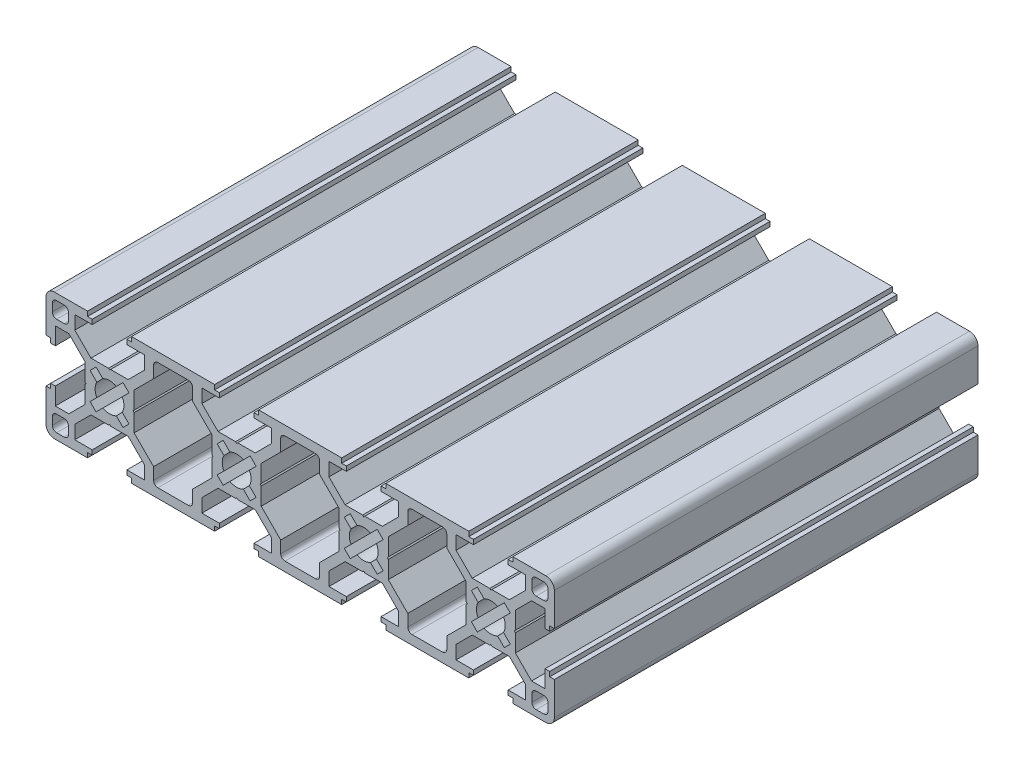
SolidWorks part; units mm, degrees
material "Aluminium"
ref_plane "Front Plane" through (0, 0, 0) normal (0, 0, 1) x (1, 0, 0)
ref_plane "Top Plane" through (0, 0, 0) normal (0, 1, 0) x (1, 0, 0)
ref_plane "Right Plane" through (0, 0, 0) normal (1, 0, 0) x (0, 0, -1)
sketch "Sketch1" plane through (0, 0, 0) normal (0, 0, 1) x (1, 0, 0)
  line L0 (-58.5, 10.7) -> (-58.5, 12.5)
  line L1 (-57.5, 13.5) -> (-55.7, 13.5)
  line L2 (-54.7, 12.5) -> (-54.7, 10.7)
  line L3 (-55.7, 9.7) -> (-57.5, 9.7)
  line L4 (-41.9951, -1.5907) -> (-40.4041, -3.1817)
  line L5 (-40.4041, -3.1817) -> (-41.8183, -4.5959)
  line L6 (-41.8183, -4.5959) -> (-43.4093, -3.0049)
  line L7 (-46.5907, -3.0049) -> (-48.1817, -4.5959)
  line L8 (-48.1817, -4.5959) -> (-49.5959, -3.1817)
  line L9 (-49.5959, -3.1817) -> (-48.0049, -1.5907)
  line L10 (-48.0049, 1.5907) -> (-49.5959, 3.1817)
  line L11 (-49.5959, 3.1817) -> (-48.1817, 4.5959)
  line L12 (-48.1817, 4.5959) -> (-46.5907, 3.0049)
  line L13 (-43.4093, 3.0049) -> (-41.8183, 4.5959)
  line L14 (-41.8183, 4.5959) -> (-40.4041, 3.1817)
  line L15 (-40.4041, 3.1817) -> (-41.9951, 1.5907)
  line L16 (-58.5, -12.5) -> (-58.5, -10.7)
  line L17 (-57.5, -9.7) -> (-55.7, -9.7)
  line L18 (-54.7, -10.7) -> (-54.7, -12.5)
  line L19 (-55.7, -13.5) -> (-57.5, -13.5)
  line L20 (-20.55, 0) -> (-20.8, -0.25)
  line L21 (-20.8, -0.25) -> (-20.8, -4.3858)
  line L22 (-20.8, -4.3858) -> (-25.4, -8.9858)
  line L23 (-25.4, -8.9858) -> (-25.4, -11.8)
  line L24 (-26.4, -12.8) -> (-33.6, -12.8)
  line L25 (-34.6, -11.8) -> (-34.6, -8.9858)
  line L26 (-34.6, -8.9858) -> (-39.2, -4.3858)
  line L27 (-39.2, -4.3858) -> (-39.2, -0.25)
  line L28 (-39.2, -0.25) -> (-39.45, 0)
  line L29 (-39.45, 0) -> (-39.2, 0.25)
  line L30 (-39.2, 0.25) -> (-39.2, 4.3858)
  line L31 (-39.2, 4.3858) -> (-34.6, 8.9858)
  line L32 (-34.6, 8.9858) -> (-34.6, 11.8)
  line L33 (-33.6, 12.8) -> (-26.4, 12.8)
  line L34 (-25.4, 11.8) -> (-25.4, 8.9858)
  line L35 (-25.4, 8.9858) -> (-20.8, 4.3858)
  line L36 (-20.8, 4.3858) -> (-20.8, 0.25)
  line L37 (-20.8, 0.25) -> (-20.55, 0)
  line L38 (-11.9951, -1.5907) -> (-10.4041, -3.1817)
  line L39 (-10.4041, -3.1817) -> (-11.8183, -4.5959)
  line L40 (-11.8183, -4.5959) -> (-13.4093, -3.0049)
  line L41 (-16.5907, -3.0049) -> (-18.1817, -4.5959)
  line L42 (-18.1817, -4.5959) -> (-19.5959, -3.1817)
  line L43 (-19.5959, -3.1817) -> (-18.0049, -1.5907)
  line L44 (-18.0049, 1.5907) -> (-19.5959, 3.1817)
  line L45 (-19.5959, 3.1817) -> (-18.1817, 4.5959)
  line L46 (-18.1817, 4.5959) -> (-16.5907, 3.0049)
  line L47 (-13.4093, 3.0049) -> (-11.8183, 4.5959)
  line L48 (-11.8183, 4.5959) -> (-10.4041, 3.1817)
  line L49 (-10.4041, 3.1817) -> (-11.9951, 1.5907)
  line L50 (11.9951, 1.5907) -> (10.4041, 3.1817)
  line L51 (10.4041, 3.1817) -> (11.8183, 4.5959)
  line L52 (11.8183, 4.5959) -> (13.4093, 3.0049)
  line L53 (16.5907, 3.0049) -> (18.1817, 4.5959)
  line L54 (18.1817, 4.5959) -> (19.5959, 3.1817)
  line L55 (19.5959, 3.1817) -> (18.0049, 1.5907)
  line L56 (18.0049, -1.5907) -> (19.5959, -3.1817)
  line L57 (19.5959, -3.1817) -> (18.1817, -4.5959)
  line L58 (18.1817, -4.5959) -> (16.5907, -3.0049)
  line L59 (13.4093, -3.0049) -> (11.8183, -4.5959)
  line L60 (11.8183, -4.5959) -> (10.4041, -3.1817)
  line L61 (10.4041, -3.1817) -> (11.9951, -1.5907)
  line L62 (20.8, -0.25) -> (20.55, 0)
  line L63 (20.55, 0) -> (20.8, 0.25)
  line L64 (20.8, 0.25) -> (20.8, 4.3858)
  line L65 (20.8, 4.3858) -> (25.4, 8.9858)
  line L66 (25.4, 8.9858) -> (25.4, 11.8)
  line L67 (26.4, 12.8) -> (33.6, 12.8)
  line L68 (34.6, 11.8) -> (34.6, 8.9858)
  line L69 (34.6, 8.9858) -> (39.2, 4.3858)
  line L70 (39.2, 4.3858) -> (39.2, 0.25)
  line L71 (39.2, 0.25) -> (39.45, 0)
  line L72 (39.45, 0) -> (39.2, -0.25)
  line L73 (39.2, -0.25) -> (39.2, -4.3858)
  line L74 (39.2, -4.3858) -> (34.6, -8.9858)
  line L75 (34.6, -8.9858) -> (34.6, -11.8)
  line L76 (33.6, -12.8) -> (26.4, -12.8)
  line L77 (25.4, -11.8) -> (25.4, -8.9858)
  line L78 (25.4, -8.9858) -> (20.8, -4.3858)
  line L79 (20.8, -4.3858) -> (20.8, -0.25)
  line L80 (58.5, -10.7) -> (58.5, -12.5)
  line L81 (57.5, -13.5) -> (55.7, -13.5)
  line L82 (54.7, -12.5) -> (54.7, -10.7)
  line L83 (55.7, -9.7) -> (57.5, -9.7)
  line L84 (41.9951, 1.5907) -> (40.4041, 3.1817)
  line L85 (40.4041, 3.1817) -> (41.8183, 4.5959)
  line L86 (41.8183, 4.5959) -> (43.4093, 3.0049)
  line L87 (46.5907, 3.0049) -> (48.1817, 4.5959)
  line L88 (48.1817, 4.5959) -> (49.5959, 3.1817)
  line L89 (49.5959, 3.1817) -> (48.0049, 1.5907)
  line L90 (48.0049, -1.5907) -> (49.5959, -3.1817)
  line L91 (49.5959, -3.1817) -> (48.1817, -4.5959)
  line L92 (48.1817, -4.5959) -> (46.5907, -3.0049)
  line L93 (43.4093, -3.0049) -> (41.8183, -4.5959)
  line L94 (41.8183, -4.5959) -> (40.4041, -3.1817)
  line L95 (40.4041, -3.1817) -> (41.9951, -1.5907)
  line L96 (58.5, 12.5) -> (58.5, 10.7)
  line L97 (57.5, 9.7) -> (55.7, 9.7)
  line L98 (54.7, 10.7) -> (54.7, 12.5)
  line L99 (55.7, 13.5) -> (57.5, 13.5)
  line L100 (3.6, -12.8) -> (-3.6, -12.8)
  line L101 (-4.6, -11.8) -> (-4.6, -8.9858)
  line L102 (-4.6, -8.9858) -> (-9.2, -4.3858)
  line L103 (-9.2, -4.3858) -> (-9.2, -0.25)
  line L104 (-9.2, -0.25) -> (-9.45, 0)
  line L105 (-9.45, 0) -> (-9.2, 0.25)
  line L106 (-9.2, 0.25) -> (-9.2, 4.3858)
  line L107 (-9.2, 4.3858) -> (-4.6, 8.9858)
  line L108 (-4.6, 8.9858) -> (-4.6, 11.8)
  line L109 (-3.6, 12.8) -> (3.6, 12.8)
  line L110 (4.6, 11.8) -> (4.6, 8.9858)
  line L111 (4.6, 8.9858) -> (9.2, 4.3858)
  line L112 (9.2, 4.3858) -> (9.2, 0.25)
  line L113 (9.2, 0.25) -> (9.45, 0)
  line L114 (9.45, 0) -> (9.2, -0.25)
  line L115 (9.2, -0.25) -> (9.2, -4.3858)
  line L116 (9.2, -4.3858) -> (4.6, -8.9858)
  line L117 (4.6, -8.9858) -> (4.6, -11.8)
  line L118 (-9.8, -15) -> (9.8, -15)
  line L119 (9.8, -15) -> (9.8, -13.9)
  line L120 (9.8, -13.9) -> (10.9, -13.9)
  line L121 (10.9, -13.9) -> (10.9, -12.8)
  line L122 (10.9, -12.8) -> (6.8, -12.8)
  line L123 (6.8, -12.8) -> (6.8, -9.6142)
  line L124 (6.8, -9.6142) -> (10.6142, -5.8)
  line L125 (10.6142, -5.8) -> (14.75, -5.8)
  line L126 (14.75, -5.8) -> (15, -5.55)
  line L127 (15, -5.55) -> (15.25, -5.8)
  line L128 (15.25, -5.8) -> (19.3858, -5.8)
  line L129 (19.3858, -5.8) -> (23.2, -9.6142)
  line L130 (23.2, -9.6142) -> (23.2, -12.8)
  line L131 (23.2, -12.8) -> (19.1, -12.8)
  line L132 (19.1, -12.8) -> (19.1, -13.9)
  line L133 (19.1, -13.9) -> (20.2, -13.9)
  line L134 (20.2, -13.9) -> (20.2, -15)
  line L135 (20.2, -15) -> (39.8, -15)
  line L136 (39.8, -15) -> (39.8, -13.9)
  line L137 (39.8, -13.9) -> (40.9, -13.9)
  line L138 (40.9, -13.9) -> (40.9, -12.8)
  line L139 (40.9, -12.8) -> (36.8, -12.8)
  line L140 (36.8, -12.8) -> (36.8, -9.6142)
  line L141 (36.8, -9.6142) -> (40.6142, -5.8)
  line L142 (40.6142, -5.8) -> (44.75, -5.8)
  line L143 (44.75, -5.8) -> (45, -5.55)
  line L144 (45, -5.55) -> (45.25, -5.8)
  line L145 (45.25, -5.8) -> (49.3858, -5.8)
  line L146 (49.3858, -5.8) -> (53.2, -9.6142)
  line L147 (53.2, -9.6142) -> (53.2, -12.8)
  line L148 (53.2, -12.8) -> (49.1, -12.8)
  line L149 (49.1, -12.8) -> (49.1, -13.9)
  line L150 (49.1, -13.9) -> (50.2, -13.9)
  line L151 (50.2, -13.9) -> (50.2, -15)
  line L152 (50.2, -15) -> (58, -15)
  line L153 (60, -13) -> (60, -5.2)
  line L154 (60, -5.2) -> (58.9, -5.2)
  line L155 (58.9, -5.2) -> (58.9, -4.1)
  line L156 (58.9, -4.1) -> (57.8, -4.1)
  line L157 (57.8, -4.1) -> (57.8, -8.2)
  line L158 (57.8, -8.2) -> (54.6142, -8.2)
  line L159 (54.6142, -8.2) -> (50.8, -4.3858)
  line L160 (50.8, -4.3858) -> (50.8, -0.25)
  line L161 (50.8, -0.25) -> (50.55, 0)
  line L162 (50.55, 0) -> (50.8, 0.25)
  line L163 (50.8, 0.25) -> (50.8, 4.3858)
  line L164 (50.8, 4.3858) -> (54.6142, 8.2)
  line L165 (54.6142, 8.2) -> (57.8, 8.2)
  line L166 (57.8, 8.2) -> (57.8, 4.1)
  line L167 (57.8, 4.1) -> (58.9, 4.1)
  line L168 (58.9, 4.1) -> (58.9, 5.2)
  line L169 (58.9, 5.2) -> (60, 5.2)
  line L170 (60, 5.2) -> (60, 13)
  line L171 (58, 15) -> (50.2, 15)
  line L172 (50.2, 15) -> (50.2, 13.9)
  line L173 (50.2, 13.9) -> (49.1, 13.9)
  line L174 (49.1, 13.9) -> (49.1, 12.8)
  line L175 (49.1, 12.8) -> (53.2, 12.8)
  line L176 (53.2, 12.8) -> (53.2, 9.6142)
  line L177 (53.2, 9.6142) -> (49.3858, 5.8)
  line L178 (49.3858, 5.8) -> (45.25, 5.8)
  line L179 (45.25, 5.8) -> (45, 5.55)
  line L180 (45, 5.55) -> (44.75, 5.8)
  line L181 (44.75, 5.8) -> (40.6142, 5.8)
  line L182 (40.6142, 5.8) -> (36.8, 9.6142)
  line L183 (36.8, 9.6142) -> (36.8, 12.8)
  line L184 (36.8, 12.8) -> (40.9, 12.8)
  line L185 (40.9, 12.8) -> (40.9, 13.9)
  line L186 (40.9, 13.9) -> (39.8, 13.9)
  line L187 (39.8, 13.9) -> (39.8, 15)
  line L188 (39.8, 15) -> (20.2, 15)
  line L189 (20.2, 15) -> (20.2, 13.9)
  line L190 (20.2, 13.9) -> (19.1, 13.9)
  line L191 (19.1, 13.9) -> (19.1, 12.8)
  line L192 (19.1, 12.8) -> (23.2, 12.8)
  line L193 (23.2, 12.8) -> (23.2, 9.6142)
  line L194 (23.2, 9.6142) -> (19.3858, 5.8)
  line L195 (19.3858, 5.8) -> (15.25, 5.8)
  line L196 (15.25, 5.8) -> (15, 5.55)
  line L197 (15, 5.55) -> (14.75, 5.8)
  line L198 (14.75, 5.8) -> (10.6142, 5.8)
  line L199 (10.6142, 5.8) -> (6.8, 9.6142)
  line L200 (6.8, 9.6142) -> (6.8, 12.8)
  line L201 (6.8, 12.8) -> (10.9, 12.8)
  line L202 (10.9, 12.8) -> (10.9, 13.9)
  line L203 (10.9, 13.9) -> (9.8, 13.9)
  line L204 (9.8, 13.9) -> (9.8, 15)
  line L205 (9.8, 15) -> (-9.8, 15)
  line L206 (-9.8, 15) -> (-9.8, 13.9)
  line L207 (-9.8, 13.9) -> (-10.9, 13.9)
  line L208 (-10.9, 13.9) -> (-10.9, 12.8)
  line L209 (-10.9, 12.8) -> (-6.8, 12.8)
  line L210 (-6.8, 12.8) -> (-6.8, 9.6142)
  line L211 (-6.8, 9.6142) -> (-10.6142, 5.8)
  line L212 (-10.6142, 5.8) -> (-14.75, 5.8)
  line L213 (-14.75, 5.8) -> (-15, 5.55)
  line L214 (-15, 5.55) -> (-15.25, 5.8)
  line L215 (-15.25, 5.8) -> (-19.3858, 5.8)
  line L216 (-19.3858, 5.8) -> (-23.2, 9.6142)
  line L217 (-23.2, 9.6142) -> (-23.2, 12.8)
  line L218 (-23.2, 12.8) -> (-19.1, 12.8)
  line L219 (-19.1, 12.8) -> (-19.1, 13.9)
  line L220 (-19.1, 13.9) -> (-20.2, 13.9)
  line L221 (-20.2, 13.9) -> (-20.2, 15)
  line L222 (-20.2, 15) -> (-39.8, 15)
  line L223 (-39.8, 15) -> (-39.8, 13.9)
  line L224 (-39.8, 13.9) -> (-40.9, 13.9)
  line L225 (-40.9, 13.9) -> (-40.9, 12.8)
  line L226 (-40.9, 12.8) -> (-36.8, 12.8)
  line L227 (-36.8, 12.8) -> (-36.8, 9.6142)
  line L228 (-36.8, 9.6142) -> (-40.6142, 5.8)
  line L229 (-40.6142, 5.8) -> (-44.75, 5.8)
  line L230 (-44.75, 5.8) -> (-45, 5.55)
  line L231 (-45, 5.55) -> (-45.25, 5.8)
  line L232 (-45.25, 5.8) -> (-49.3858, 5.8)
  line L233 (-49.3858, 5.8) -> (-53.2, 9.6142)
  line L234 (-53.2, 9.6142) -> (-53.2, 12.8)
  line L235 (-53.2, 12.8) -> (-49.1, 12.8)
  line L236 (-49.1, 12.8) -> (-49.1, 13.9)
  line L237 (-49.1, 13.9) -> (-50.2, 13.9)
  line L238 (-50.2, 13.9) -> (-50.2, 15)
  line L239 (-50.2, 15) -> (-58, 15)
  line L240 (-60, 13) -> (-60, 5.2)
  line L241 (-60, 5.2) -> (-58.9, 5.2)
  line L242 (-58.9, 5.2) -> (-58.9, 4.1)
  line L243 (-58.9, 4.1) -> (-57.8, 4.1)
  line L244 (-57.8, 4.1) -> (-57.8, 8.2)
  line L245 (-57.8, 8.2) -> (-54.6142, 8.2)
  line L246 (-54.6142, 8.2) -> (-50.8, 4.3858)
  line L247 (-50.8, 4.3858) -> (-50.8, 0.25)
  line L248 (-50.8, 0.25) -> (-50.55, 0)
  line L249 (-50.55, 0) -> (-50.8, -0.25)
  line L250 (-50.8, -0.25) -> (-50.8, -4.3858)
  line L251 (-50.8, -4.3858) -> (-54.6142, -8.2)
  line L252 (-54.6142, -8.2) -> (-57.8, -8.2)
  line L253 (-57.8, -8.2) -> (-57.8, -4.1)
  line L254 (-57.8, -4.1) -> (-58.9, -4.1)
  line L255 (-58.9, -4.1) -> (-58.9, -5.2)
  line L256 (-58.9, -5.2) -> (-60, -5.2)
  line L257 (-60, -5.2) -> (-60, -13)
  line L258 (-58, -15) -> (-50.2, -15)
  line L259 (-50.2, -15) -> (-50.2, -13.9)
  line L260 (-50.2, -13.9) -> (-49.1, -13.9)
  line L261 (-49.1, -13.9) -> (-49.1, -12.8)
  line L262 (-49.1, -12.8) -> (-53.2, -12.8)
  line L263 (-53.2, -12.8) -> (-53.2, -9.6142)
  line L264 (-53.2, -9.6142) -> (-49.3858, -5.8)
  line L265 (-49.3858, -5.8) -> (-45.25, -5.8)
  line L266 (-45.25, -5.8) -> (-45, -5.55)
  line L267 (-45, -5.55) -> (-44.75, -5.8)
  line L268 (-44.75, -5.8) -> (-40.6142, -5.8)
  line L269 (-40.6142, -5.8) -> (-36.8, -9.6142)
  line L270 (-36.8, -9.6142) -> (-36.8, -12.8)
  line L271 (-36.8, -12.8) -> (-40.9, -12.8)
  line L272 (-40.9, -12.8) -> (-40.9, -13.9)
  line L273 (-40.9, -13.9) -> (-39.8, -13.9)
  line L274 (-39.8, -13.9) -> (-39.8, -15)
  line L275 (-39.8, -15) -> (-20.2, -15)
  line L276 (-20.2, -15) -> (-20.2, -13.9)
  line L277 (-20.2, -13.9) -> (-19.1, -13.9)
  line L278 (-19.1, -13.9) -> (-19.1, -12.8)
  line L279 (-19.1, -12.8) -> (-23.2, -12.8)
  line L280 (-23.2, -12.8) -> (-23.2, -9.6142)
  line L281 (-23.2, -9.6142) -> (-19.3858, -5.8)
  line L282 (-19.3858, -5.8) -> (-15.25, -5.8)
  line L283 (-15.25, -5.8) -> (-15, -5.55)
  line L284 (-15, -5.55) -> (-14.75, -5.8)
  line L285 (-14.75, -5.8) -> (-10.6142, -5.8)
  line L286 (-10.6142, -5.8) -> (-6.8, -9.6142)
  line L287 (-6.8, -9.6142) -> (-6.8, -12.8)
  line L288 (-6.8, -12.8) -> (-10.9, -12.8)
  line L289 (-10.9, -12.8) -> (-10.9, -13.9)
  line L290 (-10.9, -13.9) -> (-9.8, -13.9)
  line L291 (-9.8, -13.9) -> (-9.8, -15)
  arc A0 (-58.5, 12.5) -> (-57.5, 13.5) centre (-57.5, 12.5) cw
  arc A1 (-55.7, 13.5) -> (-54.7, 12.5) centre (-55.7, 12.5) cw
  arc A2 (-54.7, 10.7) -> (-55.7, 9.7) centre (-55.7, 10.7) cw
  arc A3 (-57.5, 9.7) -> (-58.5, 10.7) centre (-57.5, 10.7) cw
  arc A4 (-41.9951, 1.5907) -> (-41.9951, -1.5907) centre (-45, 0) cw
  arc A5 (-43.4093, -3.0049) -> (-46.5907, -3.0049) centre (-45, 0) cw
  arc A6 (-48.0049, -1.5907) -> (-48.0049, 1.5907) centre (-45, 0) cw
  arc A7 (-46.5907, 3.0049) -> (-43.4093, 3.0049) centre (-45, 0) cw
  arc A8 (-58.5, -10.7) -> (-57.5, -9.7) centre (-57.5, -10.7) cw
  arc A9 (-55.7, -9.7) -> (-54.7, -10.7) centre (-55.7, -10.7) cw
  arc A10 (-54.7, -12.5) -> (-55.7, -13.5) centre (-55.7, -12.5) cw
  arc A11 (-57.5, -13.5) -> (-58.5, -12.5) centre (-57.5, -12.5) cw
  arc A12 (-25.4, -11.8) -> (-26.4, -12.8) centre (-26.4, -11.8) cw
  arc A13 (-33.6, -12.8) -> (-34.6, -11.8) centre (-33.6, -11.8) cw
  arc A14 (-34.6, 11.8) -> (-33.6, 12.8) centre (-33.6, 11.8) cw
  arc A15 (-26.4, 12.8) -> (-25.4, 11.8) centre (-26.4, 11.8) cw
  arc A16 (-11.9951, 1.5907) -> (-11.9951, -1.5907) centre (-15, 0) cw
  arc A17 (-13.4093, -3.0049) -> (-16.5907, -3.0049) centre (-15, 0) cw
  arc A18 (-18.0049, -1.5907) -> (-18.0049, 1.5907) centre (-15, 0) cw
  arc A19 (-16.5907, 3.0049) -> (-13.4093, 3.0049) centre (-15, 0) cw
  arc A20 (11.9951, -1.5907) -> (11.9951, 1.5907) centre (15, 0) cw
  arc A21 (13.4093, 3.0049) -> (16.5907, 3.0049) centre (15, 0) cw
  arc A22 (18.0049, 1.5907) -> (18.0049, -1.5907) centre (15, 0) cw
  arc A23 (16.5907, -3.0049) -> (13.4093, -3.0049) centre (15, 0) cw
  arc A24 (25.4, 11.8) -> (26.4, 12.8) centre (26.4, 11.8) cw
  arc A25 (33.6, 12.8) -> (34.6, 11.8) centre (33.6, 11.8) cw
  arc A26 (34.6, -11.8) -> (33.6, -12.8) centre (33.6, -11.8) cw
  arc A27 (26.4, -12.8) -> (25.4, -11.8) centre (26.4, -11.8) cw
  arc A28 (58.5, -12.5) -> (57.5, -13.5) centre (57.5, -12.5) cw
  arc A29 (55.7, -13.5) -> (54.7, -12.5) centre (55.7, -12.5) cw
  arc A30 (54.7, -10.7) -> (55.7, -9.7) centre (55.7, -10.7) cw
  arc A31 (57.5, -9.7) -> (58.5, -10.7) centre (57.5, -10.7) cw
  arc A32 (41.9951, -1.5907) -> (41.9951, 1.5907) centre (45, 0) cw
  arc A33 (43.4093, 3.0049) -> (46.5907, 3.0049) centre (45, 0) cw
  arc A34 (48.0049, 1.5907) -> (48.0049, -1.5907) centre (45, 0) cw
  arc A35 (46.5907, -3.0049) -> (43.4093, -3.0049) centre (45, 0) cw
  arc A36 (58.5, 10.7) -> (57.5, 9.7) centre (57.5, 10.7) cw
  arc A37 (55.7, 9.7) -> (54.7, 10.7) centre (55.7, 10.7) cw
  arc A38 (54.7, 12.5) -> (55.7, 13.5) centre (55.7, 12.5) cw
  arc A39 (57.5, 13.5) -> (58.5, 12.5) centre (57.5, 12.5) cw
  arc A40 (-3.6, -12.8) -> (-4.6, -11.8) centre (-3.6, -11.8) cw
  arc A41 (-4.6, 11.8) -> (-3.6, 12.8) centre (-3.6, 11.8) cw
  arc A42 (3.6, 12.8) -> (4.6, 11.8) centre (3.6, 11.8) cw
  arc A43 (4.6, -11.8) -> (3.6, -12.8) centre (3.6, -11.8) cw
  arc A44 (58, -15) -> (60, -13) centre (58, -13) ccw
  arc A45 (60, 13) -> (58, 15) centre (58, 13) ccw
  arc A46 (-58, 15) -> (-60, 13) centre (-58, 13) ccw
  arc A47 (-60, -13) -> (-58, -15) centre (-58, -13) ccw
extrude "Boss-Extrude1" add sketch "Sketch1" against normal mid plane 100
